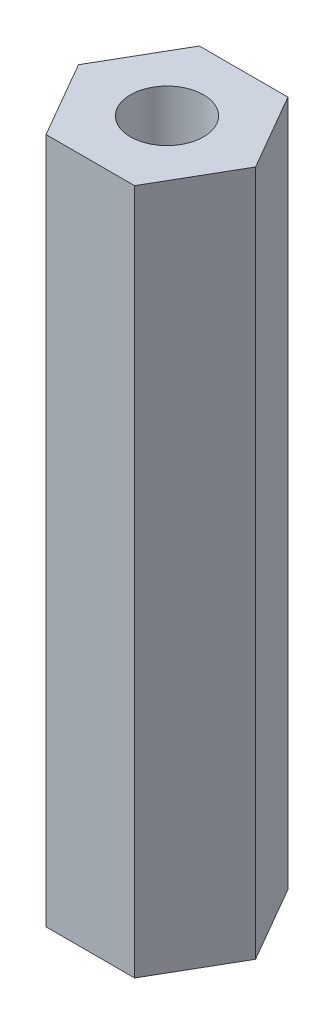
SolidWorks part; units mm, degrees
ref_plane "Front Plane" through (0, 0, 0) normal (0, 0, 1) x (1, 0, 0)
ref_plane "Top Plane" through (0, 0, 0) normal (0, 1, 0) x (1, 0, 0)
ref_plane "Right Plane" through (0, 0, 0) normal (1, 0, 0) x (0, 0, -1)
sketch "Sketch1" plane through (0, 0, 0) normal (0, 1, 0) x (1, 0, 0)
  line L1 (4, 0) -> (2, 3.4641)
  line L2 (2, 3.4641) -> (-2, 3.4641)
  line L3 (-2, 3.4641) -> (-4, 0)
  line L4 (-4, 0) -> (-2, -3.4641)
  line L5 (-2, -3.4641) -> (2, -3.4641)
  line L6 (2, -3.4641) -> (4, 0)
  circle A0 centre (0, 0) radius 4 construction
extrude "Boss-Extrude1" add sketch "Sketch1" along normal blind 31
hole_wizard "Tap Drill for M4x0.7 Tap1" positions "Sketch3" profile "Sketch2" hole size "M4x0.7" standard "ANSI Metric" end condition through all
sketch "Sketch3" plane through (0, 31, 0) normal (0, 1, 0) x (1, 0, 0)
  point P0 (0, 0)
sketch "Sketch2" plane through (0, 31, 0) normal (1, 0, 0) x (0, 0, 1)
  line L0 (0, 0) -> (0, 31)
  line L1 (0, 31) -> (1.65, 31)
  line L2 (1.65, 31) -> (1.65, 0)
  line L5 (1.65, 0) -> (0, 0)
  line L11 (0, -6.35) -> (0, 107.95) construction
  dimension "Thru Hole Dia." = 3.3
  dimension "Thru Hole Depth" = 31
